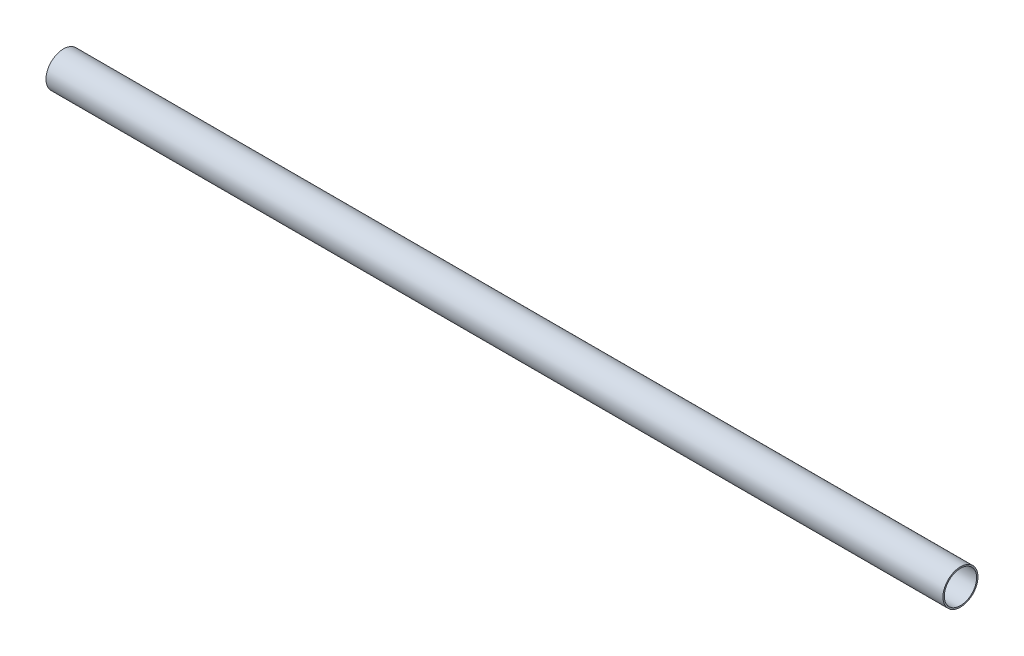
SolidWorks part; units mm, degrees
material "Acero al carbono no aleado"
ref_plane "Alzado" through (0, 0, 0) normal (0, 0, 1) x (1, 0, 0)
ref_plane "Planta" through (0, 0, 0) normal (0, 1, 0) x (1, 0, 0)
ref_plane "Vista lateral" through (0, 0, 0) normal (1, 0, 0) x (0, 0, -1)
sketch "Croquis1" plane through (0, 0, 0) normal (1, 0, 0) x (0, 0, -1)
  circle A0 centre (0, 0) radius 25.4
  circle A1 centre (0, 0) radius 23.4
  dimension "D1" = 50.8
  dimension "D2" = 2
extrude "Saliente-Extruir1" add sketch "Croquis1" along normal mid plane 1300
